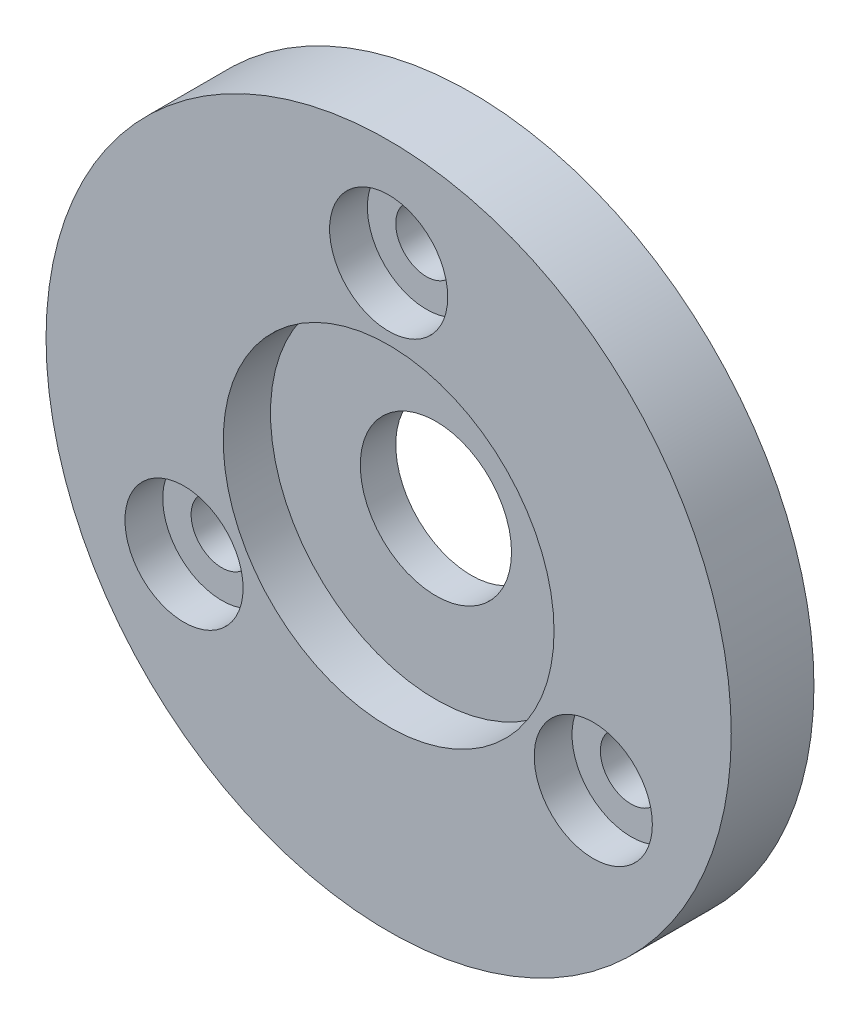
SolidWorks part; units mm, degrees
ref_plane "정면" through (0, 0, 0) normal (0, 0, 1) x (1, 0, 0)
ref_plane "윗면" through (0, 0, 0) normal (0, 1, 0) x (1, 0, 0)
ref_plane "우측면" through (0, 0, 0) normal (1, 0, 0) x (0, 0, -1)
sketch "스케치1" plane through (0, 0, 0) normal (0, 0, 1) x (1, 0, 0)
  circle A0 centre (0, 0) radius 14.5
  dimension "D1" = 29
extrude "보스-돌출2" add sketch "스케치1" along normal blind 3.5
sketch "스케치4" plane through (0, 0, 3.5) normal (0, 0, 1) x (1, 0, 0)
  circle A0 centre (0, 0) radius 3.2
  dimension "D1" = 6.4
extrude "컷-돌출1" cut sketch "스케치4" against normal through all
sketch "스케치5" plane through (0, 0, 3.5) normal (0, 0, 1) x (1, 0, 0)
  line L0 (0, 10) -> (0, 0) construction
  line L1 (0, 0) -> (-8.6603, -5) construction
  line L2 (0, 0) -> (8.6603, -5) construction
  circle A0 centre (0, 0) radius 10 construction
  point P7 (0, 10)
  point P8 (8.6603, -5)
  point P9 (-8.6603, -5)
  dimension "D1" = 20
  dimension "D2" = 120
  dimension "D3" = 120
hole_wizard "M2 남비 머리 나사용 카운터보어1" positions "3D스케치1" profile "스케치6" counterbore size "M2" standard "ISO"
sketch3d "3D스케치1"
  point P0 (0, 10, 3.5)
  point P3 (-8.6603, -5, 3.5)
  point P6 (8.6603, -5, 3.5)
sketch "스케치6" plane through (0, 10, 3.5) normal (1, 0, 0) x (0, -1, 0)
  line L0 (0, 0) -> (0, 5.7811)
  line L1 (0, 5.7811) -> (1.3, 5)
  line L2 (1.3, 5) -> (1.3, 1.6)
  line L3 (1.3, 1.6) -> (2.5, 1.6)
  line L4 (2.5, 1.6) -> (2.5, 0)
  line L5 (2.5, 0) -> (0, 0)
  line L10 (0, 5.7811) -> (-1.3, 5) construction
  line L11 (0, -6.35) -> (0, 107.95) construction
  dimension "구멍 지름" = 2.6
  dimension "구멍 깊이" = 5
  dimension "카운터보어 지름" = 5
  dimension "카운터보어 깊이" = 1.6
  dimension "드릴 각도" = 118
sketch "스케치7" plane through (0, 0, 3.5) normal (0, 0, 1) x (1, 0, 0)
  circle A0 centre (0, 0) radius 7
  dimension "D1" = 14
extrude "컷-돌출2" cut sketch "스케치7" against normal blind 2
